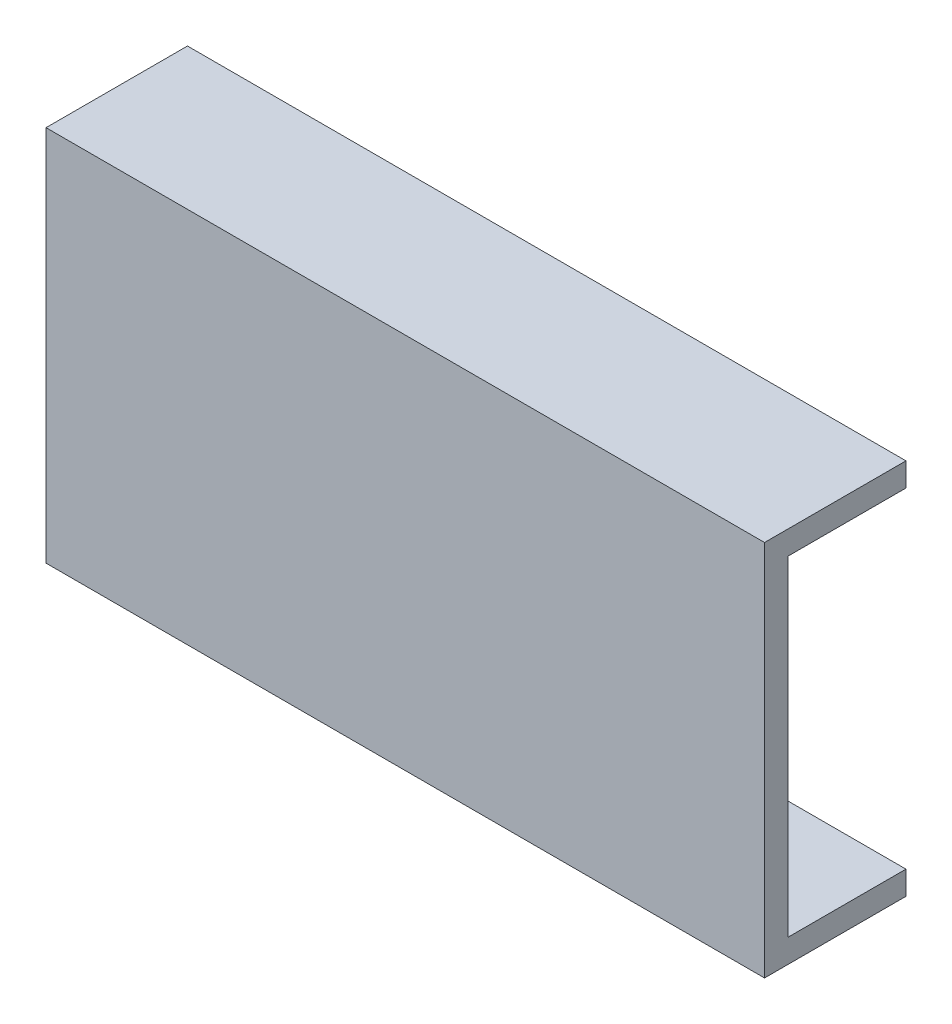
SolidWorks part; units mm, degrees
ref_plane "Front Plane" through (0, 0, 0) normal (0, 0, 1) x (1, 0, 0)
ref_plane "Top Plane" through (0, 0, 0) normal (0, 1, 0) x (1, 0, 0)
ref_plane "Right Plane" through (0, 0, 0) normal (1, 0, 0) x (0, 0, -1)
sketch "Sketch1" plane through (0, 0, 0) normal (1, 0, 0) x (0, 0, -1)
  line L0 (0, 65.8376) -> (30, 65.8376)
  line L1 (30, 65.8376) -> (30, 60.8376)
  line L2 (30, 60.8376) -> (5, 60.8376)
  line L3 (5, 60.8376) -> (5, -9.1624)
  line L4 (5, -9.1624) -> (30, -9.1624)
  line L5 (30, -9.1624) -> (30, -14.1624)
  line L6 (30, -14.1624) -> (0, -14.1624)
  line L7 (0, -14.1624) -> (0, 65.8376)
  dimension "D1" = 5
  dimension "D2" = 80
  dimension "D3" = 5
  dimension "D4" = 30
extrude "Boss-Extrude1" add sketch "Sketch1" along normal blind 152.4
